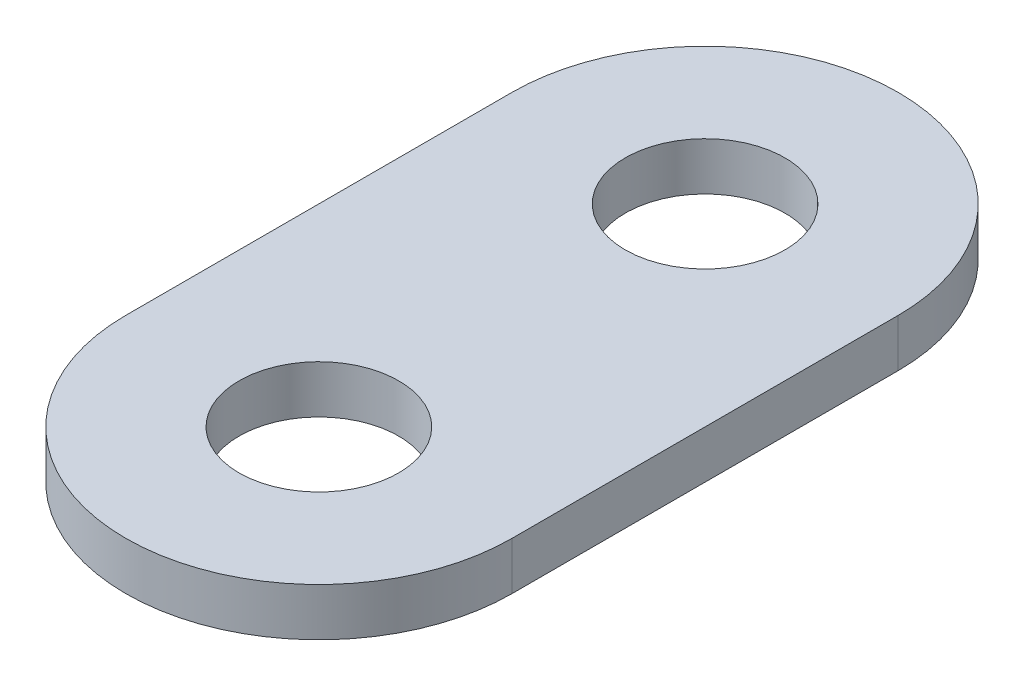
SolidWorks part; units mm, degrees
ref_plane "Front Plane" through (0, 0, 0) normal (0, 0, 1) x (1, 0, 0)
ref_plane "Top Plane" through (0, 0, 0) normal (0, 1, 0) x (1, 0, 0)
ref_plane "Right Plane" through (0, 0, 0) normal (1, 0, 0) x (0, 0, -1)
sketch "Sketch1" plane through (0, 0, 0) normal (0, 1, 0) x (1, 0, 0)
  line L0 (0, 0) -> (0, 15) construction
  line L5 (-7.5, 0) -> (-7.5, 15)
  line L6 (7.5, 0) -> (7.5, 15)
  circle A0 centre (0, 0) radius 3.1
  arc A1 (-7.5, 0) -> (7.5, 0) centre (0, 0) ccw
  arc A2 (7.5, 15) -> (-7.5, 15) centre (0, 15) ccw
  circle A3 centre (0, 15) radius 3.1
  point P3 (0, 7.5)
  dimension "D1" = 6.2
  dimension "D2" = 15
  dimension "D3" = 15
extrude "Boss-Extrude1" add sketch "Sketch1" along normal blind 0.86 and the other way blind 1
